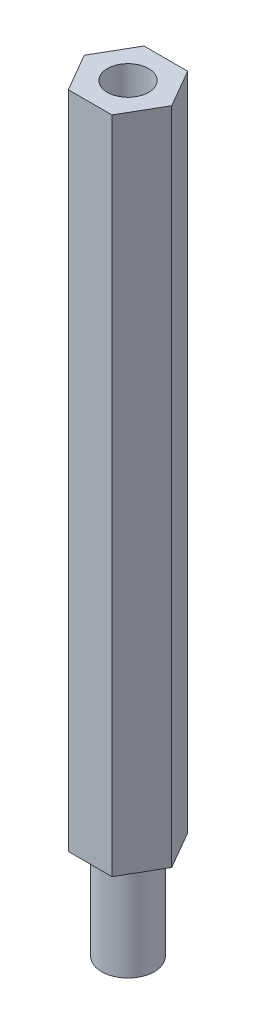
SolidWorks part; units mm, degrees
ref_plane "前视基准面" through (0, 0, 0) normal (0, 0, 1) x (1, 0, 0)
ref_plane "上视基准面" through (0, 0, 0) normal (0, 1, 0) x (1, 0, 0)
ref_plane "右视基准面" through (0, 0, 0) normal (1, 0, 0) x (0, 0, -1)
sketch "草图4" plane through (0, 0, 0) normal (0, 1, 0) x (1, 0, 0)
  line L0 (-12.7945, 0) -> (16.3015, 0) construction
  line L2 (1.325, -2.295) -> (2.65, 0)
  line L3 (2.65, 0) -> (1.325, 2.295)
  line L4 (1.325, 2.295) -> (-1.325, 2.295)
  line L5 (-1.325, 2.295) -> (-2.65, 0)
  line L6 (-2.65, 0) -> (-1.325, -2.295)
  line L7 (-1.325, -2.295) -> (1.325, -2.295)
  circle A0 centre (0, 0) radius 2.295 construction
  dimension "D1" = 5.3
extrude "凸台-拉伸1" add sketch "草图4" along normal blind 40
sketch "草图6" plane through (0, 0, 0) normal (0, -1, 0) x (-1, 0, 0)
  circle A0 centre (0, 0) radius 1.6
  dimension "D1" = 3.2
extrude "凸台-拉伸2" add sketch "草图6" along normal blind 6
cosmetic thread "装饰螺纹线1" parameters "D2"=2.5
sketch "草图7" plane through (0, 40, 0) normal (0, 1, 0) x (1, 0, 0)
  circle A0 centre (0, 0) radius 1.25
  dimension "D1" = 2.5
extrude "切除-拉伸1" cut sketch "草图7" against normal blind 5
cosmetic thread "装饰螺纹线2" parameters "D2"=3
